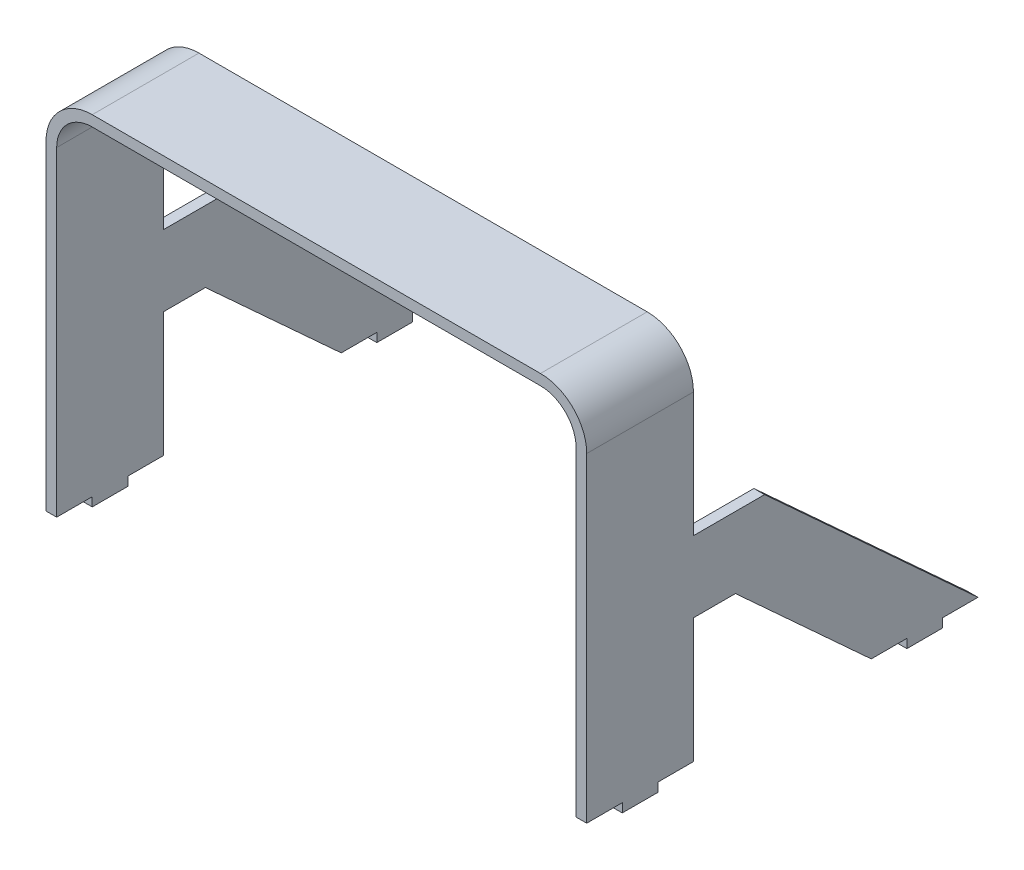
SolidWorks part; units mm, degrees
material "5052-H32"
ref_plane "Front Plane" through (0, 0, 0) normal (0, 0, 1) x (1, 0, 0)
ref_plane "Top Plane" through (0, 0, 0) normal (0, 1, 0) x (1, 0, 0)
ref_plane "Right Plane" through (0, 0, 0) normal (1, 0, 0) x (0, 0, -1)
sketch "Sketch1" plane through (0, 0, 0) normal (0, 0, 1) x (1, 0, 0)
  line L0 (-93, 0) -> (93, 0) construction
  line L1 (-73, 0) -> (-73, 90)
  line L2 (-63, 100) -> (63, 100)
  line L3 (73, 90) -> (73, 0)
  line L4 (-76, 0) -> (-76, 90)
  line L5 (-63, 103) -> (63, 103)
  line L6 (76, 90) -> (76, 0)
  line L7 (-76, 0) -> (-73, 0)
  line L8 (73, 0) -> (76, 0)
  arc A0 (63, 100) -> (73, 90) centre (63, 90) cw
  arc A1 (-73, 90) -> (-63, 100) centre (-63, 90) cw
  arc A2 (-76, 90) -> (-63, 103) centre (-63, 90) cw
  arc A3 (63, 103) -> (76, 90) centre (63, 90) cw
  point P2 (0, 0)
  dimension "D5" = 10
  dimension "D1" = 186
  dimension "D2" = 20
  dimension "D3" = 20
  dimension "D4" = 100
  dimension "D6" = 3
extrude "Boss-Extrude1" add sketch "Sketch1" along normal blind 30
sketch "Sketch2" plane through (0, 0, 0) normal (1, 0, 0) x (0, 0, -1)
  line L0 (0, 55) -> (20, 55)
  line L1 (0, 0) -> (0, 90) construction
  line L2 (20, 55) -> (80, 0)
  line L3 (80, 0) -> (50, 0)
  line L4 (50, 0) -> (11.8182, 35)
  line L5 (11.8182, 35) -> (0, 35)
  line L6 (0, 55) -> (0, 35)
  dimension "D1" = 50
  dimension "D2" = 30
  dimension "D3" = 35
  dimension "D4" = 20
  dimension "D5" = 20
extrude "Boss-Extrude2" add sketch "Sketch2" along normal blind 3 from offset 73
mirror "Mirror1" about plane through (0, 0, 0) normal (1, 0, 0) of "Boss-Extrude2"
sketch "Sketch3" plane through (0, 0, 0) normal (0, -1, 0) x (1, 0, 0)
  line L1 (-76, 20) -> (-73, 20)
  line L2 (-76, 20) -> (-76, 10)
  line L3 (-76, 10) -> (-73, 10)
  line L4 (-73, 20) -> (-73, 10)
  line L5 (-76, 20) -> (-73, 10) construction
  line L6 (-76, 10) -> (-73, 20) construction
  line L10 (-73, 30) -> (-73, 0) construction
  line L11 (-73, 30) -> (-73, 0) construction
  line L12 (-76, -60) -> (-73, -60)
  line L13 (-76, -60) -> (-76, -70)
  line L14 (-76, -70) -> (-73, -70)
  line L15 (-73, -60) -> (-73, -70)
  line L16 (-76, -60) -> (-73, -70) construction
  line L17 (-76, -70) -> (-73, -60) construction
  line L22 (-73, -50) -> (-73, -80) construction
  line L23 (0, 0) -> (0, -50000) construction
  line L24 (76, -70) -> (73, -60) construction
  line L25 (76, -60) -> (73, -70) construction
  line L26 (76, 10) -> (73, 20) construction
  line L27 (76, 20) -> (73, 10) construction
  line L28 (73, -60) -> (73, -70)
  line L29 (76, -70) -> (73, -70)
  line L30 (76, -60) -> (76, -70)
  line L31 (76, -60) -> (73, -60)
  line L32 (73, 20) -> (73, 10)
  line L33 (76, 10) -> (73, 10)
  line L34 (76, 20) -> (76, 10)
  line L35 (76, 20) -> (73, 20)
  point P4 (-74.5, 15)
  point P5 (-73, 15)
  point P6 (-73, 15)
  point P9 (-73, -65)
  point P14 (-74.5, -65)
  point P17 (-73, -65)
  point P31 (73, -65)
  point P32 (74.5, -65)
  point P33 (73, 15)
  point P34 (74.5, 15)
  dimension "D1" = 3
  dimension "D2" = 10
  dimension "D3" = 3
  dimension "D6" = 10
extrude "Boss-Extrude3" add sketch "Sketch3" along normal blind 2.5
